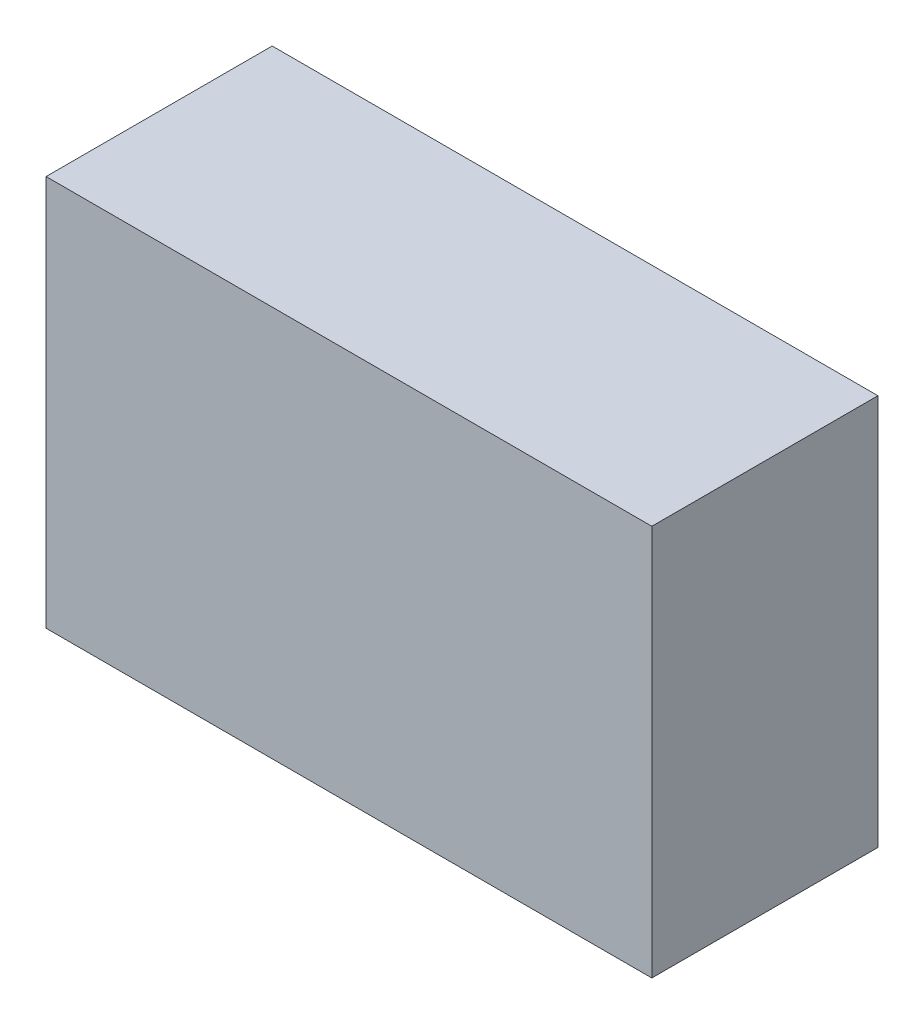
SolidWorks part; units mm, degrees
ref_plane "Front Plane" through (0, 0, 0) normal (0, 0, 1) x (1, 0, 0)
ref_plane "Top Plane" through (0, 0, 0) normal (0, 1, 0) x (1, 0, 0)
ref_plane "Right Plane" through (0, 0, 0) normal (1, 0, 0) x (0, 0, -1)
sketch "Sketch2" plane through (0, 0, 0) normal (0, 0, 1) x (1, 0, 0)
  line L1 (0, 0) -> (288, 0)
  line L2 (0, 0) -> (0, 186)
  line L3 (0, 186) -> (288, 186)
  line L4 (288, 0) -> (288, 186)
  dimension "D1" = 288
  dimension "D2" = 186
extrude "Boss-Extrude1" add sketch "Sketch2" along normal blind 107.5
ref_plane "Plane1" through (144, 0, 0) normal (1, 0, 0) x (0, 0, -1)
